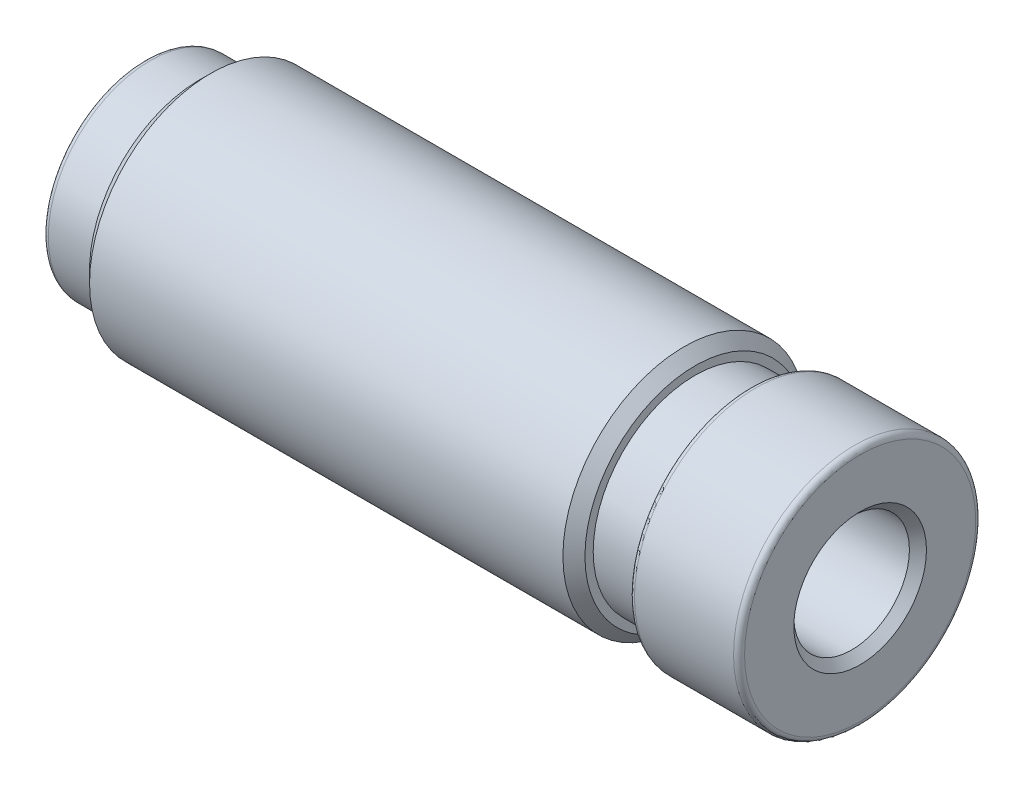
SolidWorks part; units mm, degrees
ref_plane "Plano frontal" through (0, 0, 0) normal (0, 0, 1) x (1, 0, 0)
ref_plane "Plano superior" through (0, 0, 0) normal (0, 1, 0) x (1, 0, 0)
ref_plane "Plano direito" through (0, 0, 0) normal (1, 0, 0) x (0, 0, -1)
sketch "Esboço1" plane through (0, 0, 0) normal (0, 0, 1) x (1, 0, 0)
  line L0 (0, 0) -> (65, 0)
  line L1 (65, 0) -> (65, 11)
  line L2 (65, 11) -> (55, 11)
  line L3 (55, 11) -> (55, 9.25)
  line L4 (55, 9.25) -> (50, 9.25)
  line L5 (50, 9.25) -> (50, 11)
  line L6 (50, 11) -> (5, 11)
  line L7 (5, 11) -> (5, 9.25)
  line L8 (5, 9.25) -> (0, 9.25)
  line L9 (0, 9.25) -> (0, 0)
  point P2 (27.5, 11)
  point P11 (60, 11)
  dimension "D1" = 11
  dimension "D2" = 10
  dimension "D3" = 5
  dimension "D4" = 5
  dimension "D5" = 65
  dimension "D6" = 9.25
  dimension "D7" = 9.25
  dimension "D8" = 45
revolve "Revolução1" add sketch "Esboço1" angle 360 about L0
cosmetic thread "Representação de rosca1" parameters "D1"=45, "D2"=19.797
hole_wizard "Furo roscado de M12x1.51" positions "Esboço2" profile "Esboço3" tap size "M12x1.5" standard "DIN"
sketch "Esboço2" plane through (65, 0, 0) normal (1, 0, 0) x (0, 0, -1)
  point P0 (0, 0)
sketch "Esboço3" plane through (65, 0, 0) normal (0, 1, 0) x (0, 0, -1)
  line L0 (0, 0) -> (0, 44.6545)
  line L1 (0, 44.6545) -> (5.25, 41.5)
  line L2 (5.25, 41.5) -> (5.25, 0.775)
  line L3 (5.25, 0.775) -> (6.025, 0)
  line L5 (6.025, 0) -> (0, 0)
  line L6 (-5.25, 0.775) -> (-6.025, 0) construction
  line L10 (0, 44.6545) -> (-5.25, 41.5) construction
  line L11 (0, -6.35) -> (0, 107.95) construction
  dimension "Tap Drill Dia." = 10.5
  dimension "Tap Drill Depth" = 41.5
  dimension "Near C'Sink Dia." = 12.05
  dimension "Near C'Sink Angle" = 90
  dimension "Drill Angle" = 118
cosmetic thread "Rosca de furo1" parameters "D1"=34, "D2"=12
hole_wizard "Furo1" positions "Esboço4" profile "Esboço5" legacy
sketch "Esboço4" plane through (0, 0, 0) normal (-1, 0, 0) x (0, 0, 1)
  point P0 (0, 0)
sketch "Esboço5" plane through (0, 0, 0) normal (0, 1, 0) x (0, 0, 1)
  line L0 (0, 0) -> (0, 25)
  line L1 (0, 25) -> (4.9, 25)
  line L2 (4.9, 25) -> (4.9, 0)
  line L3 (4.9, 0) -> (0, 0)
  line L4 (0, 110) -> (0, -10) construction
  dimension "Diameter" = 9.8
  dimension "Depth" = 25
chamfer "Chanfro1" distance 1 angle 45 1 edges at (5, 0, 11)
chamfer "Chanfro3" distance 1 angle 45 1 edges at (50, 0, 11)
fillet "Filete1" radius 0.5 3 edges at (0, 0, 9.25) (65, 0, 11) (55, 0, 11)
chamfer "Chanfro4" distance 0.5 angle 45 1 edges at (0, 0, 4.9)
